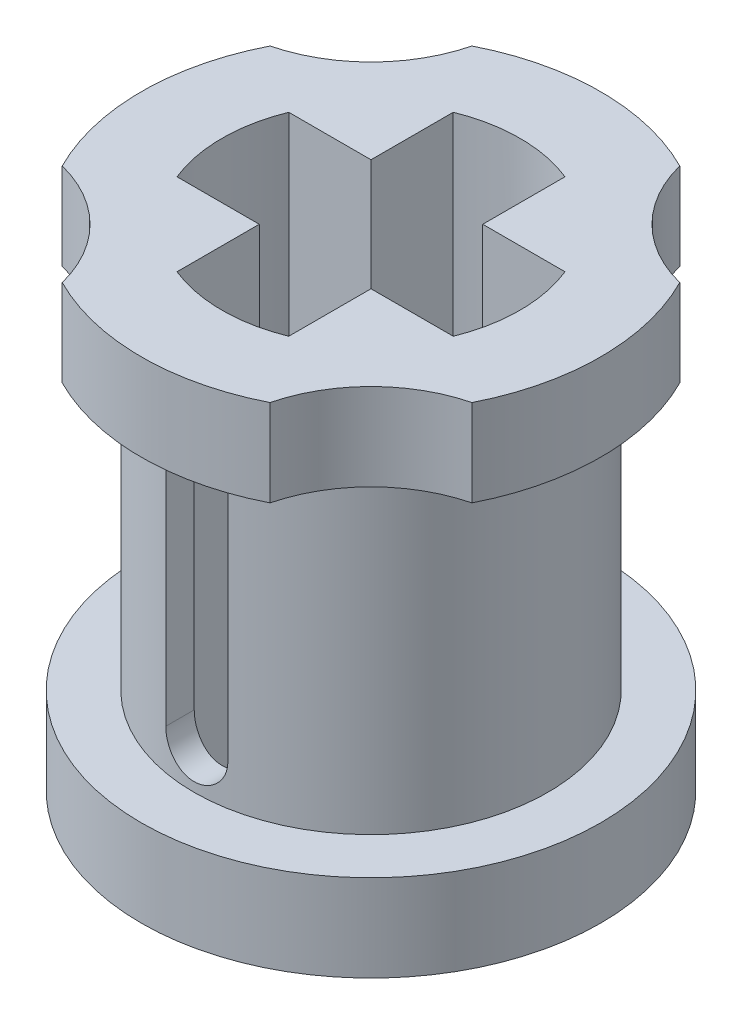
SolidWorks part; units mm, degrees
ref_plane "Front Plane" through (0, 0, 0) normal (0, 0, 1) x (1, 0, 0)
ref_plane "Top Plane" through (0, 0, 0) normal (0, 1, 0) x (1, 0, 0)
ref_plane "Right Plane" through (0, 0, 0) normal (1, 0, 0) x (0, 0, -1)
sketch "Sketch1" plane through (0, 0, 0) normal (0, 1, 0) x (1, 0, 0)
  circle A0 centre (0, 0) radius 2.85
  dimension "D1" = 5.7
extrude "Middle Body" add sketch "Sketch1" along normal mid plane 5.1
sketch "Sketch2" plane through (0, -2.55, 0) normal (0, -1, 0) x (1, 0, 0)
  circle A0 centre (0, 0) radius 3.7
  dimension "D1" = 7.4
extrude "Outer Rim" add sketch "Sketch2" along normal blind 1.4
mirror "Mirror1" about plane through (0, 0, 0) normal (0, 1, 0) of "Outer Rim"
sketch "Sketch3" plane through (0, 0, 0) normal (0, 1, 0) x (1, 0, 0)
  line L1 (2.4, -0.9) -> (-2.4, -0.9)
  line L2 (2.4, -0.9) -> (2.4, 0.9)
  line L3 (2.4, 0.9) -> (-2.4, 0.9)
  line L4 (-2.4, -0.9) -> (-2.4, 0.9)
  line L5 (2.4, -0.9) -> (-2.4, 0.9) construction
  line L6 (2.4, 0.9) -> (-2.4, -0.9) construction
  line L7 (0.9, -2.4) -> (-0.9, -2.4)
  line L8 (0.9, -2.4) -> (0.9, 2.4)
  line L9 (0.9, 2.4) -> (-0.9, 2.4)
  line L10 (-0.9, -2.4) -> (-0.9, 2.4)
  line L11 (0.9, -2.4) -> (-0.9, 2.4) construction
  line L12 (0.9, 2.4) -> (-0.9, -2.4) construction
  circle A0 centre (0, 0) radius 2.4
  dimension "D1" = 4.8
  dimension "D2" = 1.8
extrude "Axle Cut" cut sketch "Sketch3" against normal through all both and the other way through all contours L8 A0 L10 L3 | L3 A0 L1 L10 | L10 L1 L8 L3 | A0 L8 L1 L10 | L1 A0 L3 L8
sketch "Sketch4" plane through (0, 0, 0) normal (0, 0, 1) x (1, 0, 0)
  line L0 (0, -1.9) -> (0, 1.9) construction
  line L1 (-0.5, -1.9) -> (-0.5, 1.9)
  line L2 (0.5, -1.9) -> (0.5, 1.9)
  arc A0 (-0.5, -1.9) -> (0.5, -1.9) centre (0, -1.9) ccw
  arc A1 (0.5, 1.9) -> (-0.5, 1.9) centre (0, 1.9) ccw
  point P2 (0, 0)
  dimension "D2" = 4.8
  dimension "D1" = 1
extrude "Slot Cut" cut sketch "Sketch4" against normal through all both and the other way through all
sketch "Sketch5" plane through (0, 3.95, 0) normal (0, 1, 0) x (1, 0, 0)
  line L0 (0, 0) -> (3.8509, 3.8509) construction
  line L2 (0.9, 0.9) -> (0.9, 2.2249) construction
  circle A0 centre (0, 0) radius 3.2
  circle A3 centre (3.8509, 3.8509) radius 2.246
  circle A4 centre (0, 0) radius 3.7 construction
  circle A5 centre (3.8509, -3.8509) radius 2.246
  circle A6 centre (-3.8509, -3.8509) radius 2.246
  circle A7 centre (-3.8509, 3.8509) radius 2.246
  point P7 (1.6735, 3.2999)
  point P8 (3.2999, 1.6735)
  circle M23 centre (0, 0) radius 3.7
  dimension "D1" = 6.4
  dimension "D3" = 2.3
  dimension "D2" = 45
  dimension "D4" = 4
extrude "Scallop Cut " cut sketch "Sketch5" against normal blind 1.4 contours A7 M23 | L0 A3 M23 | A3 L0 M23 | A5 | A6
